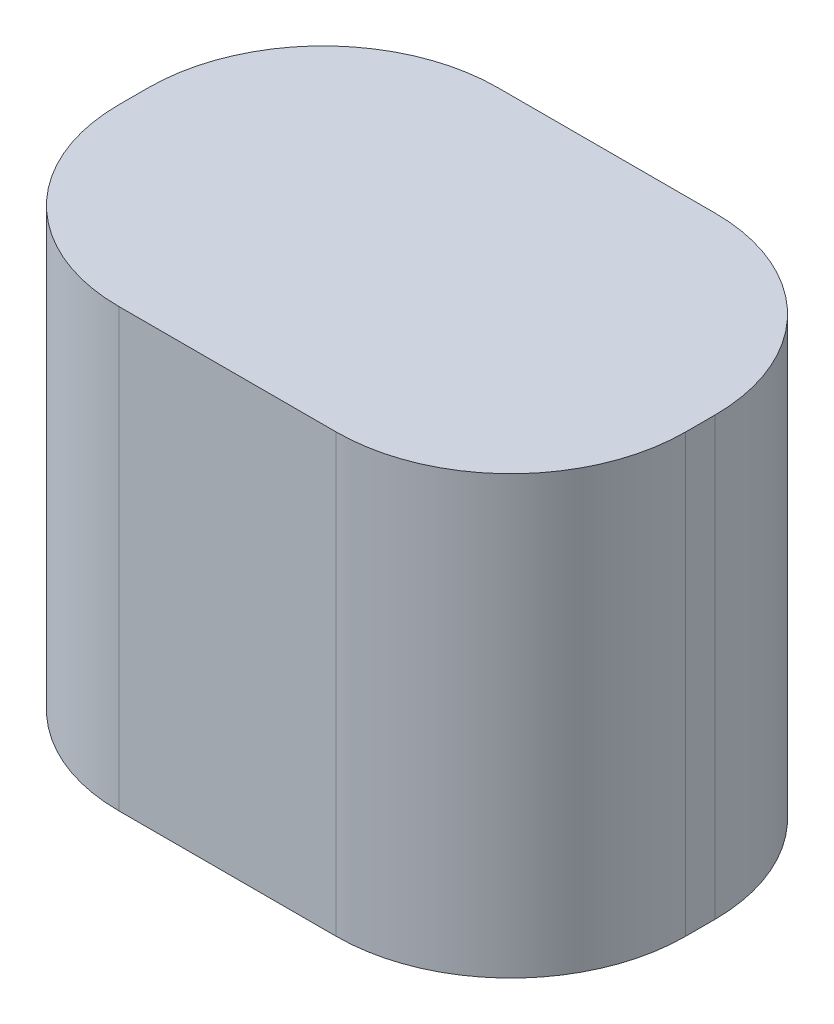
SolidWorks part; units mm, degrees
ref_plane "Front Plane" through (0, 0, 0) normal (0, 0, 1) x (1, 0, 0)
ref_plane "Top Plane" through (0, 0, 0) normal (0, 1, 0) x (1, 0, 0)
ref_plane "Right Plane" through (0, 0, 0) normal (1, 0, 0) x (0, 0, -1)
sketch "Sketch1" plane through (0, 0, 0) normal (0, 1, 0) x (1, 0, 0)
  line L1 (0, 0) -> (98.873, 0)
  line L2 (0, 0) -> (0, 66.1198)
  line L3 (0, 66.1198) -> (98.873, 66.1198)
  line L4 (98.873, 0) -> (98.873, 66.1198)
extrude "Boss-Extrude1" add sketch "Sketch1" along normal blind 76.2
fillet "Fillet1" radius 30.48 4 edges at (98.873, 38.1, -66.1198) (0, 38.1, -66.1198) (98.873, 38.1, 0) (0, 38.1, 0)
